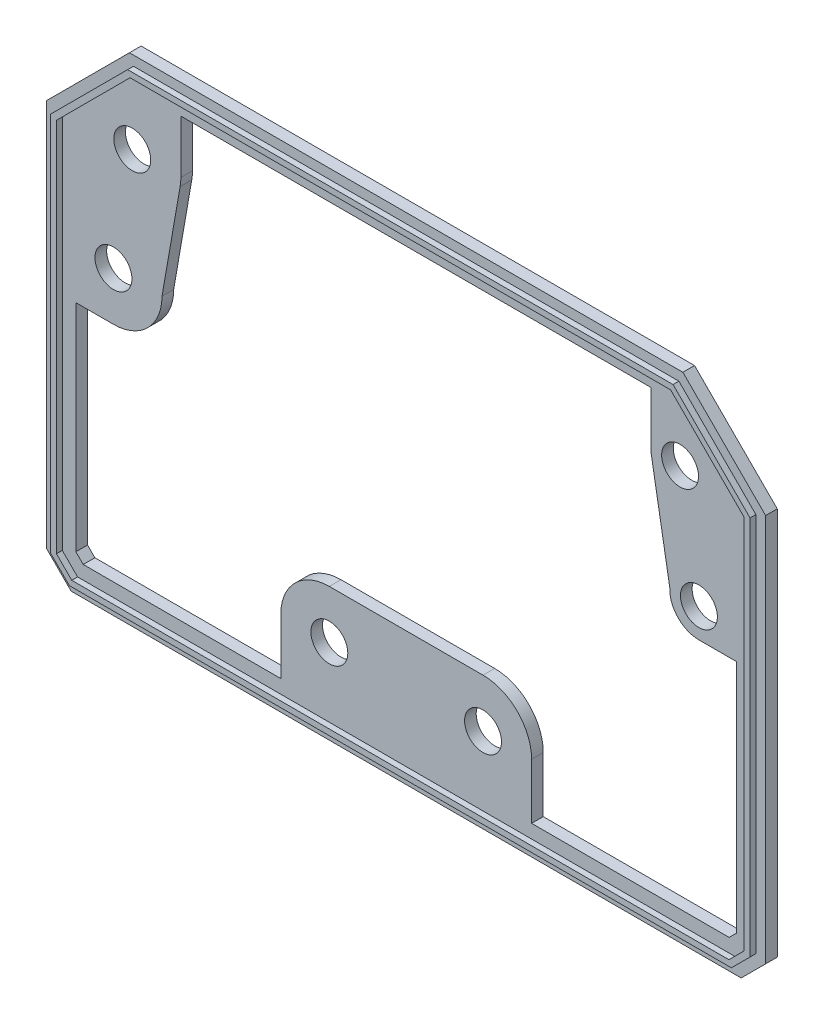
SolidWorks part; units mm, degrees
ref_plane "Front Plane" through (0, 0, 0) normal (0, 0, 1) x (1, 0, 0)
ref_plane "Top Plane" through (0, 0, 0) normal (0, 1, 0) x (1, 0, 0)
ref_plane "Right Plane" through (0, 0, 0) normal (1, 0, 0) x (0, 0, -1)
sketch "Sketch1" plane through (0, 0, 0) normal (0, 0, 1) x (1, 0, 0)
  line L8 (-68, 2.5147) -> (-65.4853, 0)
  line L9 (-65.4853, 0) -> (3.4853, 0)
  line L10 (3.4853, 0) -> (6, 2.5147)
  line L11 (6, 2.5147) -> (6, 42.4853)
  line L12 (6, 42.4853) -> (-2.5147, 51)
  line L13 (-2.5147, 51) -> (-59.4853, 51)
  line L14 (-59.4853, 51) -> (-68, 42.4853)
  line L15 (-68, 42.4853) -> (-68, 2.5147)
  line L16 (-68, 2.5147) -> (-65.4853, 0)
  line L17 (-65.4853, 0) -> (3.4853, 0)
  line L18 (3.4853, 0) -> (6, 2.5147)
  line L19 (6, 2.5147) -> (6, 42.4853)
  line L20 (6, 42.4853) -> (-2.5147, 51)
  line L21 (-2.5147, 51) -> (-59.4853, 51)
  line L22 (-59.4853, 51) -> (-68, 42.4853)
  line L23 (-68, 42.4853) -> (-68, 2.5147)
  line L32 (3, 27.9646) -> (-0.8657, 27.9646)
  line L33 (3, 27.9646) -> (-0.8657, 27.9646)
  line L34 (3, 3.7574) -> (3, 27.9646)
  line L35 (2.2426, 3) -> (3, 3.7574)
  line L36 (-18.0902, 3) -> (2.2426, 3)
  line L37 (-18.0902, 8.7108) -> (-18.0902, 3)
  line L38 (-38.9098, 13.7108) -> (-23.0902, 13.7108)
  line L39 (-43.9098, 3) -> (-43.9098, 8.7108)
  line L40 (-64.2426, 3) -> (-43.9098, 3)
  line L41 (-65, 3.7574) -> (-64.2426, 3)
  line L42 (-65, 25.9646) -> (-65, 3.7574)
  line L43 (-61.1343, 25.9646) -> (-65, 25.9646)
  line L44 (-54.2697, 41.6693) -> (-56.1343, 30.9646)
  line L45 (-54.1956, 48) -> (-54.1956, 42.5273)
  line L46 (-5.8044, 48) -> (-54.1956, 48)
  line L47 (-5.8044, 42.5273) -> (-5.8044, 48)
  line L50 (3, 3.7574) -> (3, 27.9646)
  line L51 (2.2426, 3) -> (3, 3.7574)
  line L52 (-18.0902, 3) -> (2.2426, 3)
  line L53 (-18.0902, 8.7108) -> (-18.0902, 3)
  line L54 (-38.9098, 13.7108) -> (-23.0902, 13.7108)
  line L55 (-43.9098, 3) -> (-43.9098, 8.7108)
  line L56 (-64.2426, 3) -> (-43.9098, 3)
  line L57 (-65, 3.7574) -> (-64.2426, 3)
  line L58 (-65, 25.9646) -> (-65, 3.7574)
  line L59 (-61.1343, 25.9646) -> (-65, 25.9646)
  line L60 (-54.2697, 41.6693) -> (-56.1343, 30.9646)
  line L61 (-54.1956, 48) -> (-54.1956, 42.5273)
  line L62 (-5.8044, 48) -> (-54.1956, 48)
  line L112 (-5.8044, 42.5273) -> (-5.8044, 48)
  line L113 (-3.8619, 31.1156) -> (-5.7599, 42.0125)
  line L114 (-3.8619, 31.1156) -> (-5.7599, 42.0125)
  circle A1 centre (-0.8657, 30.9646) radius 1.9
  circle A2 centre (-0.8657, 30.9646) radius 1.9
  circle A3 centre (-61.1343, 30.9646) radius 1.9
  circle A4 centre (-61.1343, 30.9646) radius 1.9
  circle A5 centre (-38.9098, 8.7108) radius 1.9
  arc A6 (-5.8044, 42.5273) -> (-5.7599, 42.0125) centre (-2.8044, 42.5273) ccw
  arc A7 (-18.0902, 8.7108) -> (-23.0902, 13.7108) centre (-23.0902, 8.7108) ccw
  arc A8 (-38.9098, 13.7108) -> (-43.9098, 8.7108) centre (-38.9098, 8.7108) ccw
  arc A9 (-61.1343, 25.9646) -> (-56.1343, 30.9646) centre (-61.1343, 30.9646) ccw
  arc A10 (-54.2697, 41.6693) -> (-54.1956, 42.5273) centre (-59.1956, 42.5273) ccw
  arc A11 (-5.8044, 42.5273) -> (-5.7599, 42.0125) centre (-2.8044, 42.5273) ccw
  arc A13 (-18.0902, 8.7108) -> (-23.0902, 13.7108) centre (-23.0902, 8.7108) ccw
  arc A14 (-38.9098, 13.7108) -> (-43.9098, 8.7108) centre (-38.9098, 8.7108) ccw
  arc A15 (-61.1343, 25.9646) -> (-56.1343, 30.9646) centre (-61.1343, 30.9646) ccw
  arc A16 (-54.2697, 41.6693) -> (-54.1956, 42.5273) centre (-59.1956, 42.5273) ccw
  circle A18 centre (-38.9098, 8.7108) radius 1.9
  circle A19 centre (-23.0902, 8.7108) radius 1.9
  circle A20 centre (-23.0902, 8.7108) radius 1.9
  circle A21 centre (-2.8044, 42.5273) radius 1.9
  circle A22 centre (-2.8044, 42.5273) radius 1.9
  circle A23 centre (-59.1956, 42.5273) radius 1.9
  circle A24 centre (-59.1956, 42.5273) radius 1.9
  arc A48 (-3.8619, 31.1156) -> (-0.8657, 27.9646) centre (-0.8657, 30.9646) ccw
  arc A49 (-3.8619, 31.1156) -> (-0.8657, 27.9646) centre (-0.8657, 30.9646) ccw
  dimension "D1" = 0
  dimension "D2" = 0
  dimension "D3" = 0
  dimension "D4" = 0
  dimension "D5" = 0
  dimension "D6" = 0
  dimension "D7" = 0
  dimension "D8" = 0
extrude "Boss-Extrude1" add sketch "Sketch1" along normal blind 1.2
sketch "Sketch2" plane through (0, 0, 1.2) normal (0, 0, 1) x (1, 0, 0)
  line L8 (-66.4, 41.8225) -> (-66.4, 3.1775)
  line L9 (-66.4, 3.1775) -> (-64.8225, 1.6)
  line L10 (-64.8225, 1.6) -> (2.8225, 1.6)
  line L11 (2.8225, 1.6) -> (4.4, 3.1775)
  line L12 (4.4, 3.1775) -> (4.4, 41.8225)
  line L13 (4.4, 41.8225) -> (-3.1775, 49.4)
  line L14 (-3.1775, 49.4) -> (-58.8225, 49.4)
  line L15 (-58.8225, 49.4) -> (-66.4, 41.8225)
  line L16 (-67, 42.0711) -> (-67, 2.9289)
  line L17 (-67, 2.9289) -> (-65.0711, 1)
  line L18 (-65.0711, 1) -> (3.0711, 1)
  line L19 (3.0711, 1) -> (5, 2.9289)
  line L20 (5, 2.9289) -> (5, 42.0711)
  line L21 (5, 42.0711) -> (-2.9289, 50)
  line L22 (-2.9289, 50) -> (-59.0711, 50)
  line L23 (-59.0711, 50) -> (-67, 42.0711)
  line L24 (-67, 42.0711) -> (-67, 2.9289)
  line L25 (-67, 2.9289) -> (-65.0711, 1)
  line L26 (-65.0711, 1) -> (3.0711, 1)
  line L27 (3.0711, 1) -> (5, 2.9289)
  line L28 (5, 2.9289) -> (5, 42.0711)
  line L29 (5, 42.0711) -> (-2.9289, 50)
  line L30 (-2.9289, 50) -> (-59.0711, 50)
  line L31 (-59.0711, 50) -> (-67, 42.0711)
  dimension "D1" = 1
  dimension "D2" = 0.6
extrude "Boss-Extrude2" add sketch "Sketch2" along normal blind 0.6
